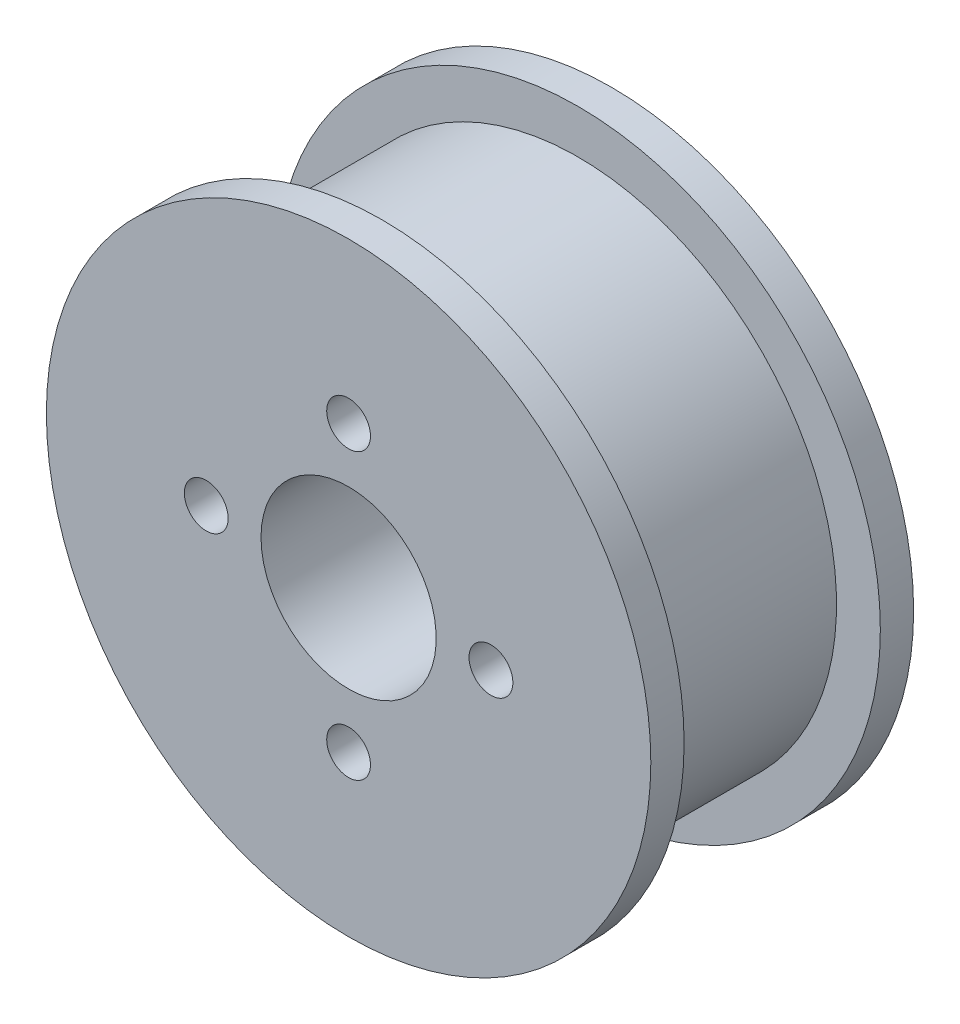
SolidWorks part; units mm, degrees
ref_plane "Front Plane" through (0, 0, 0) normal (0, 0, 1) x (1, 0, 0)
ref_plane "Top Plane" through (0, 0, 0) normal (0, 1, 0) x (1, 0, 0)
ref_plane "Right Plane" through (0, 0, 0) normal (1, 0, 0) x (0, 0, -1)
sketch "Sketch1" plane through (0, 0, 0) normal (0, 0, 1) x (1, 0, 0)
  circle A0 centre (0, 0) radius 17.25
  dimension "D1" = 34.5
extrude "Boss-Extrude1" add sketch "Sketch1" along normal blind 1.9
sketch "Sketch2" plane through (0, 0, 0) normal (0, 0, -1) x (-1, 0, 0)
  circle A0 centre (0, 0) radius 14.75
  dimension "D1" = 29.5
extrude "Boss-Extrude2" add sketch "Sketch2" along normal blind 11.2
sketch "Sketch3" plane through (0, 0, -11.2) normal (0, 0, -1) x (-1, 0, 0)
  circle A0 centre (0, 0) radius 17.25
extrude "Boss-Extrude3" add sketch "Sketch3" along normal blind 1.9
sketch "Sketch4" plane through (0, 0, -13.1) normal (0, 0, -1) x (-1, 0, 0)
  circle A0 centre (0, 0) radius 5
  dimension "D1" = 10
extrude "Cut-Extrude1" cut sketch "Sketch4" against normal through all
sketch "Sketch5" plane through (0, 0, -13.1) normal (0, 0, -1) x (-1, 0, 0)
  line L0 (0, 0) -> (8.125, 0) construction
  line L1 (0, 8.125) -> (0, 0) construction
  line L2 (0, 0) -> (-8.125, 0) construction
  line L3 (0, 0) -> (0, -8.125) construction
  circle A0 centre (0, 0) radius 11.25 construction
  circle A1 centre (0, 8.125) radius 1.25
  circle A2 centre (0, 0) radius 8.125 construction
  circle A3 centre (8.125, 0) radius 1.25
  circle A4 centre (0, -8.125) radius 1.25
  circle A5 centre (-8.125, 0) radius 1.25
  dimension "D1" = 22.5
  dimension "D2" = 16.25
  dimension "D3" = 2.5
extrude "Cut-Extrude2" cut sketch "Sketch5" against normal through all
